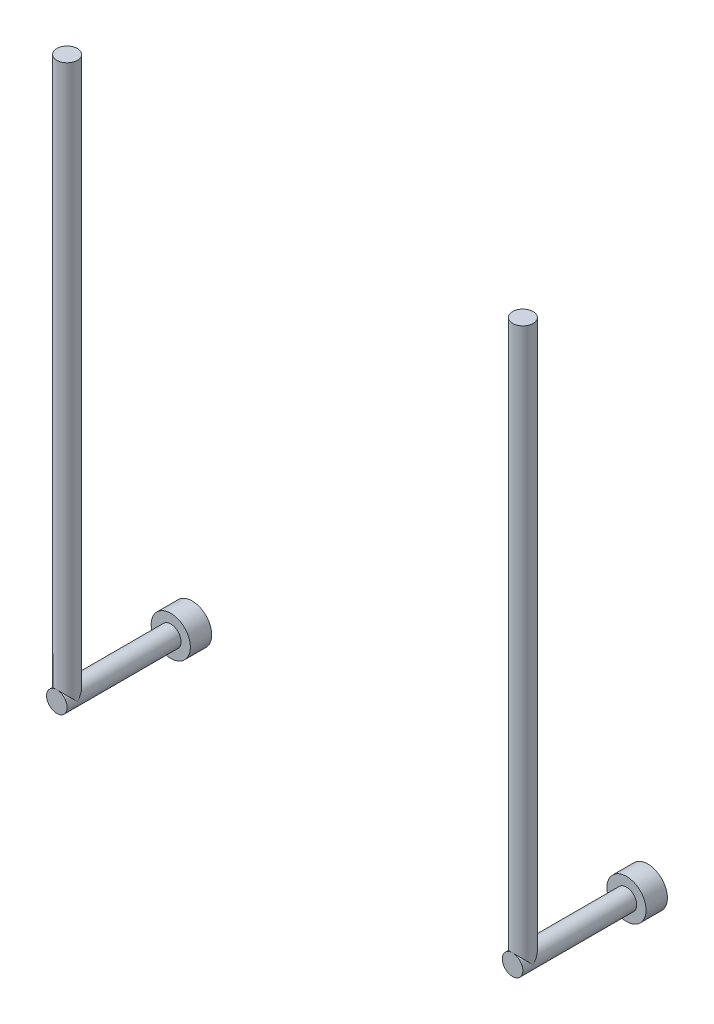
SolidWorks part; units mm, degrees
ref_plane "Front Plane" through (0, 0, 0) normal (0, 0, 1) x (1, 0, 0)
ref_plane "Top Plane" through (0, 0, 0) normal (0, 1, 0) x (1, 0, 0)
ref_plane "Right Plane" through (0, 0, 0) normal (1, 0, 0) x (0, 0, -1)
ref_plane "PY14_3" through (0, 0, 14.3) normal (0, 0, 1) x (1, 0, 0)
sketch "Sketch1" plane through (0, 0, 14.3) normal (0, 0, 1) x (1, 0, 0)
  circle A0 centre (-32, -20) radius 2.75
extrude "Bolt Head -32" add sketch "Sketch1" along normal blind 3 separate body
ref_plane "PY15_31" through (0, 0, 15.31) normal (0, 0, 1) x (1, 0, 0)
sketch "Sketch2" plane through (0, 0, 15.31) normal (0, 0, 1) x (1, 0, 0)
  circle A0 centre (-32, -20) radius 1.4438
extrude "Key Short Arm -32" add sketch "Sketch2" along normal blind 17.99 separate body
ref_plane "PZm20" through (0, -20, 0) normal (0, 1, 0) x (1, 0, 0)
sketch "Sketch3" plane through (0, -20, 0) normal (0, 1, 0) x (1, 0, 0)
  circle A0 centre (-32, -31.8562) radius 1.4438
extrude "Key Long Arm -32" add sketch "Sketch3" along normal blind 78 separate body
sketch "Sketch4" plane through (0, 0, 14.3) normal (0, 0, 1) x (1, 0, 0)
  circle A0 centre (32, -20) radius 2.75
extrude "Bolt Head +32" add sketch "Sketch4" along normal blind 3 separate body
sketch "Sketch5" plane through (0, 0, 15.31) normal (0, 0, 1) x (1, 0, 0)
  circle A0 centre (32, -20) radius 1.4438
extrude "Key Short Arm +32" add sketch "Sketch5" along normal blind 17.99 separate body
sketch "Sketch6" plane through (0, -20, 0) normal (0, 1, 0) x (1, 0, 0)
  circle A0 centre (32, -31.8562) radius 1.4438
extrude "Key Long Arm +32" add sketch "Sketch6" along normal blind 78 separate body
